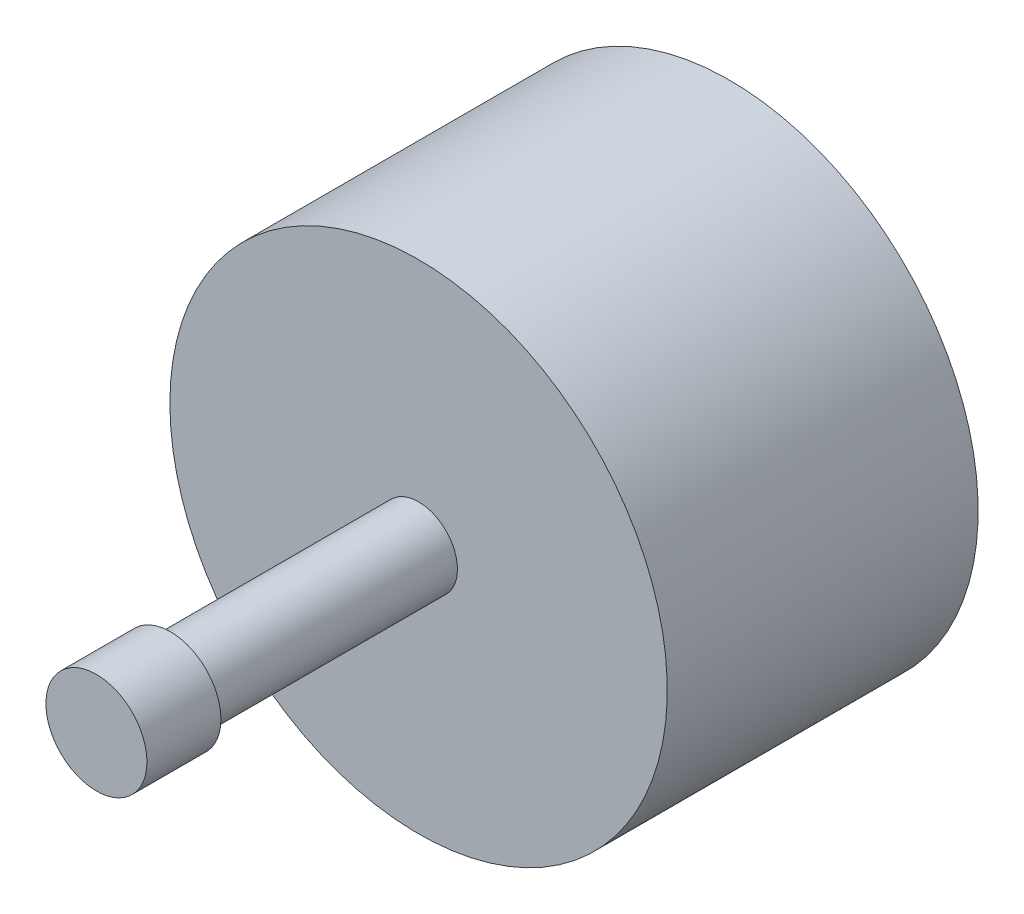
SolidWorks part; units mm, degrees
ref_plane "Plano frontal" through (0, 0, 0) normal (0, 0, 1) x (1, 0, 0)
ref_plane "Plano superior" through (0, 0, 0) normal (0, 1, 0) x (1, 0, 0)
ref_plane "Plano direito" through (0, 0, 0) normal (1, 0, 0) x (0, 0, -1)
sketch "Esboço1" plane through (0, 0, 0) normal (0, 0, 1) x (1, 0, 0)
  circle A0 centre (0, 0) radius 2.5
  dimension "D1" = 5
extrude "Ressalto-extrusão1" add sketch "Esboço1" along normal blind 15.965
sketch "Esboço2" plane through (0, 0, 15.965) normal (0, 0, 1) x (1, 0, 0)
  circle A0 centre (0, 0) radius 3.25
  dimension "D1" = 6.5
extrude "Ressalto-extrusão2" add sketch "Esboço2" along normal blind 4.76
sketch "Esboço3" plane through (0, 0, 0) normal (0, 0, -1) x (-1, 0, 0)
  circle A0 centre (0, 0) radius 16
  dimension "D1" = 32
extrude "Ressalto-extrusão3" add sketch "Esboço3" along normal blind 20
